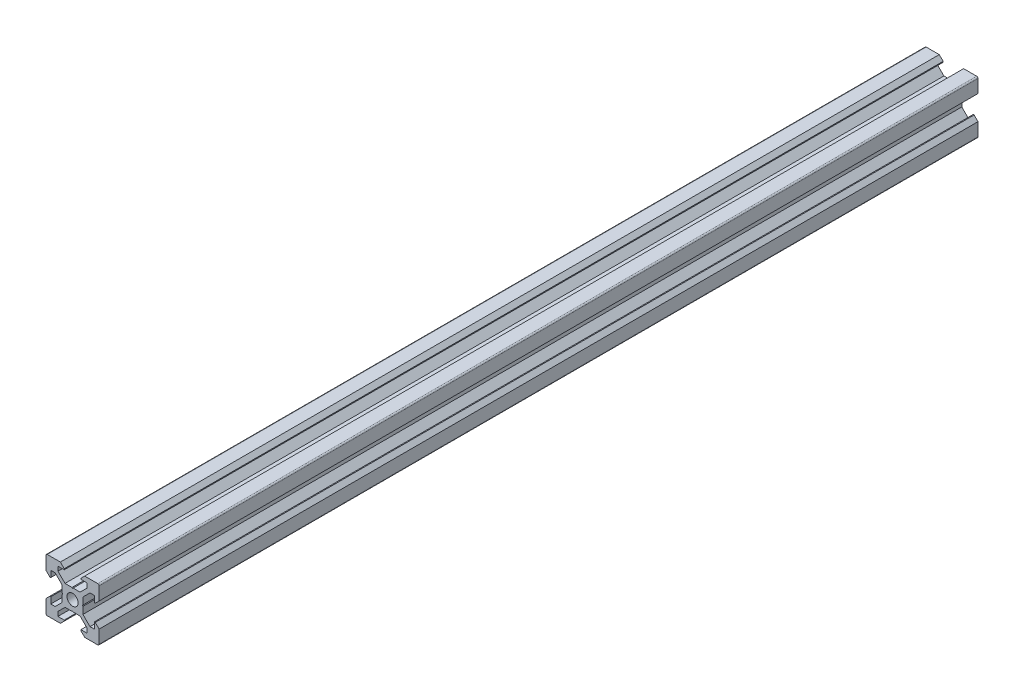
SolidWorks part; units mm, degrees
material "6061-T6 (SS)"
ref_plane "Front Plane" through (0, 0, 0) normal (0, 0, 1) x (1, 0, 0)
ref_plane "Top Plane" through (0, 0, 0) normal (0, 1, 0) x (1, 0, 0)
ref_plane "Right Plane" through (0, 0, 0) normal (1, 0, 0) x (0, 0, -1)
sketch "Sketch1" plane through (0, 0, 0) normal (0, 0, 1) x (1, 0, 0)
  line L1 (9.5, -10) -> (-9.5, -10)
  line L2 (10, -9.5) -> (10, 9.5)
  line L3 (9.5, 10) -> (-9.5, 10)
  line L4 (-10, -9.5) -> (-10, 9.5)
  line L5 (10, -10) -> (-10, 10) construction
  line L6 (10, 10) -> (-10, -10) construction
  circle A0 centre (0, 0) radius 2.1
  arc A1 (-9.5, 10) -> (-10, 9.5) centre (-9.5, 9.5) ccw
  arc A2 (10, 9.5) -> (9.5, 10) centre (9.5, 9.5) ccw
  arc A3 (9.5, -10) -> (10, -9.5) centre (9.5, -9.5) ccw
  arc A4 (-9.5, -10) -> (-10, -9.5) centre (-9.5, -9.5) cw
  point P0 (0, 0)
  line B0 (0, 0) -> (0, 10) construction
  line B1 (0, 3.69) -> (-0.21, 3.9)
  line B2 (-0.21, 3.9) -> (-2.8393, 3.9)
  line B3 (-2.8393, 3.9) -> (-5.5, 6.5607)
  line B4 (-5.5, 6.5607) -> (-5.5, 8.2)
  line B5 (-5.5, 8.2) -> (-3.125, 8.2)
  line B6 (-3.125, 8.2) -> (-3.125, 8.545)
  line B7 (-3.125, 8.545) -> (-4.58, 10)
  line B8 (-4.58, 10) -> (4.58, 10)
  line B9 (0, 0) -> (-5.9132, 5.9132) construction
  line B10 (3.125, 8.545) -> (4.58, 10)
  line B11 (3.125, 8.2) -> (3.125, 8.545)
  line B12 (5.5, 8.2) -> (3.125, 8.2)
  line B13 (5.5, 6.5607) -> (5.5, 8.2)
  line B14 (2.8393, 3.9) -> (5.5, 6.5607)
  line B15 (0.21, 3.9) -> (2.8393, 3.9)
  line B16 (0, 3.69) -> (0.21, 3.9)
  line B17 (0, 0) -> (-10, 0) construction
  line B18 (-3.69, 0) -> (-3.9, -0.21)
  line B19 (-3.9, -0.21) -> (-3.9, -2.8393)
  line B20 (-3.9, -2.8393) -> (-6.5607, -5.5)
  line B21 (-6.5607, -5.5) -> (-8.2, -5.5)
  line B22 (-8.2, -5.5) -> (-8.2, -3.125)
  line B23 (-8.2, -3.125) -> (-8.545, -3.125)
  line B24 (-8.545, -3.125) -> (-10, -4.58)
  line B25 (-10, -4.58) -> (-10, 4.58)
  line B26 (0, 0) -> (-5.9132, -5.9132) construction
  line B27 (-8.545, 3.125) -> (-10, 4.58)
  line B28 (-8.2, 3.125) -> (-8.545, 3.125)
  line B29 (-8.2, 5.5) -> (-8.2, 3.125)
  line B30 (-6.5607, 5.5) -> (-8.2, 5.5)
  line B31 (-3.9, 2.8393) -> (-6.5607, 5.5)
  line B32 (-3.9, 0.21) -> (-3.9, 2.8393)
  line B33 (-3.69, 0) -> (-3.9, 0.21)
  line B34 (0, 0) -> (0, -10) construction
  line B35 (0, -3.69) -> (0.21, -3.9)
  line B36 (0.21, -3.9) -> (2.8393, -3.9)
  line B37 (2.8393, -3.9) -> (5.5, -6.5607)
  line B38 (5.5, -6.5607) -> (5.5, -8.2)
  line B39 (5.5, -8.2) -> (3.125, -8.2)
  line B40 (3.125, -8.2) -> (3.125, -8.545)
  line B41 (3.125, -8.545) -> (4.58, -10)
  line B42 (4.58, -10) -> (-4.58, -10)
  line B43 (0, 0) -> (5.9132, -5.9132) construction
  line B44 (-3.125, -8.545) -> (-4.58, -10)
  line B45 (-3.125, -8.2) -> (-3.125, -8.545)
  line B46 (-5.5, -8.2) -> (-3.125, -8.2)
  line B47 (-5.5, -6.5607) -> (-5.5, -8.2)
  line B48 (-2.8393, -3.9) -> (-5.5, -6.5607)
  line B49 (-0.21, -3.9) -> (-2.8393, -3.9)
  line B50 (0, -3.69) -> (-0.21, -3.9)
  line B51 (0, 0) -> (10, 0) construction
  line B52 (3.69, 0) -> (3.9, 0.21)
  line B53 (3.9, 0.21) -> (3.9, 2.8393)
  line B54 (3.9, 2.8393) -> (6.5607, 5.5)
  line B55 (6.5607, 5.5) -> (8.2, 5.5)
  line B56 (8.2, 5.5) -> (8.2, 3.125)
  line B57 (8.2, 3.125) -> (8.545, 3.125)
  line B58 (8.545, 3.125) -> (10, 4.58)
  line B59 (10, 4.58) -> (10, -4.58)
  line B60 (0, 0) -> (5.9132, 5.9132) construction
  line B61 (8.545, -3.125) -> (10, -4.58)
  line B62 (8.2, -3.125) -> (8.545, -3.125)
  line B63 (8.2, -5.5) -> (8.2, -3.125)
  line B64 (6.5607, -5.5) -> (8.2, -5.5)
  line B65 (3.9, -2.8393) -> (6.5607, -5.5)
  line B66 (3.9, -0.21) -> (3.9, -2.8393)
  line B67 (3.69, 0) -> (3.9, -0.21)
  dimension "D1" = 4.2
  dimension "D3" = 0.5
  dimension "D2" = 20
sketch_block_instance "V Slot 1-4"
sketch_block "V Slot 1" parameters "D1"=10, "D2"=11, "D3"=4.3, "D4"=1.8, "D5"=0.21, "D6"=45, "D7"=9.16, "D8"=1.5, "D9"=6.25
sketch_block_instance "V Slot 1-5"
sketch_block_instance "V Slot 1-6"
sketch_block_instance "V Slot 1-7"
extrude "Boss-Extrude1" add sketch "Sketch1" along normal blind 331 contours B67 B52 B53 B54 B55 B56 B57 B58 L2 A2 L3 B10 B11 B12 B13 B14 B15 B16 B1 B2 B3 B4 B5 B6 B7 A1 L4 B27 B28 B29 B30 B31 B32 B33 B18 B19 B20 B21 B22 B23 B24 A4 L1 B44 B45 B46 B47 B48 B49
